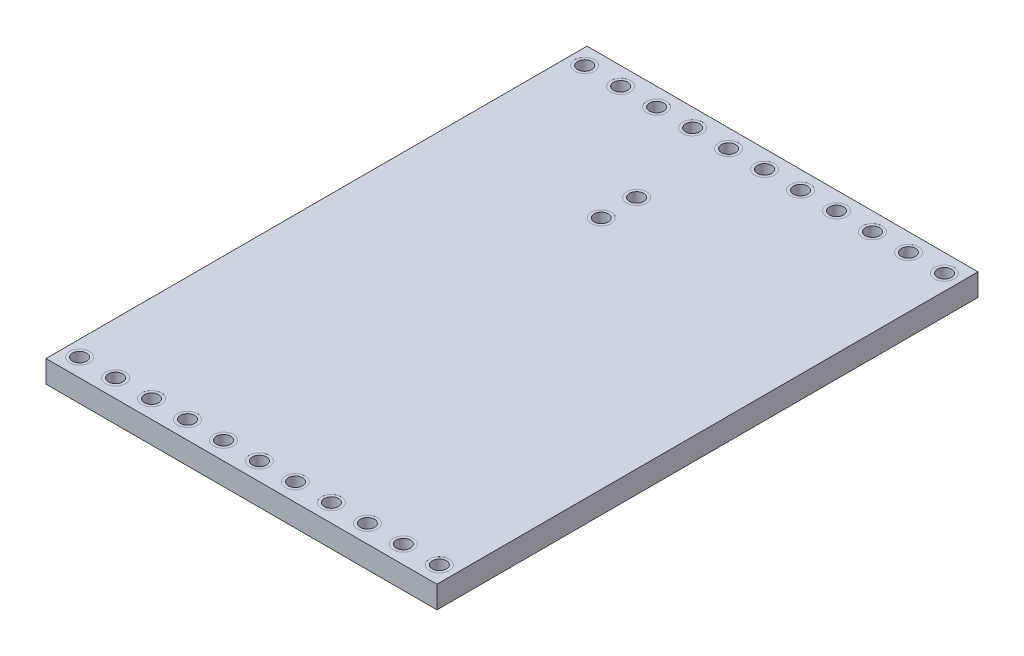
SolidWorks part; units mm, degrees
material "Power Circuit Board"
ref_plane "Front Plane" through (0, 0, 0) normal (0, 0, 1) x (1, 0, 0)
ref_plane "Top Plane" through (0, 0, 0) normal (0, 1, 0) x (1, 0, 0)
ref_plane "Right Plane" through (0, 0, 0) normal (1, 0, 0) x (0, 0, -1)
sketch "BaseS" plane through (0, 0, 0) normal (0, 1, 0) x (1, 0, 0)
  line L1 (-13.8, 19.1) -> (13.8, 19.1)
  line L2 (-13.8, 19.1) -> (-13.8, -19.1)
  line L3 (-13.8, -19.1) -> (13.8, -19.1)
  line L4 (13.8, 19.1) -> (13.8, -19.1)
  line L5 (-13.8, 19.1) -> (13.8, -19.1) construction
  line L6 (-13.8, -19.1) -> (13.8, 19.1) construction
  point P0 (0, 0)
  dimension "Width" = 27.6
  dimension "Length" = 38.2
extrude "Base" add sketch "BaseS" against normal mid plane 1.57
hole_wizard "Ø1.0 (1) Diameter Hole1" positions "Sketch2" profile "Sketch3" hole size "Ø1.0" standard "ANSI Metric" end condition through all
sketch "Sketch2" plane through (0, 0.785, 0) normal (0, 1, 0) x (1, 0, 0)
  line L0 (-13.8, 19.1) -> (-13.8, -19.1) construction
  line L1 (-13.8, -19.1) -> (13.8, -19.1) construction
  point P0 (-12.7, -17.83)
  dimension "XDim" = 1.1
  dimension "YDim" = 1.27
sketch "Sketch3" plane through (-12.7, 0.785, 17.83) normal (1, 0, 0) x (0, 0, 1)
  line L0 (0, 0) -> (0, 1.57)
  line L1 (0, 1.57) -> (0.5, 1.57)
  line L2 (0.5, 1.57) -> (0.5, 0)
  line L5 (0.5, 0) -> (0, 0)
  line L11 (0, -6.35) -> (0, 107.95) construction
  dimension "Thru Hole Dia." = 1
  dimension "Thru Hole Depth" = 1.57
sketch "SolderAccessCutS" plane through (0, 0.785, 0) normal (0, 1, 0) x (1, 0, 0)
  circle A3 centre (-12.7, -17.83) radius 0.7
  dimension "Dia" = 1.4
extrude "SolderAccessCut" cut sketch "SolderAccessCutS" against normal blind 0.001
mirror "SACVM" about plane through (0, 0, 0) normal (0, 1, 0) of "SolderAccessCut"
pattern_linear "HoleSACHorzLP" count 11 spacing 2.54 along (1, 0, 0) of "Ø1.0 (1) Diameter Hole1", "SolderAccessCut", "SACVM"
mirror "Mirror1" about plane through (0, 0, 0) normal (0, 0, 1) of "HoleSACHorzLP", "SACVM", "SolderAccessCut", "Ø1.0 (1) Diameter Hole1"
hole_wizard "Ø1.0 (1) Diameter Hole2" positions "Sketch4" profile "Sketch5" hole size "Ø1.0" standard "ANSI Metric" end condition through all
sketch "Sketch4" plane through (0, 0.785, 0) normal (0, 1, 0) x (1, 0, 0)
  line L0 (-2.8, 11.6) -> (-2.8, 9.1) construction
  line L2 (-13.8, 19.1) -> (-13.8, -19.1) construction
  line L3 (13.8, 19.1) -> (-13.8, 19.1) construction
  point P0 (-2.8, 11.6)
  point P2 (-2.8, 9.1)
  dimension "XDim" = 11
  dimension "Distance" = 2.5
  dimension "YDim" = 7.5
sketch "Sketch5" plane through (-2.8, 0.785, -11.6) normal (1, 0, 0) x (0, 0, 1)
  line L0 (0, 0) -> (0, 1.57)
  line L1 (0, 1.57) -> (0.5, 1.57)
  line L2 (0.5, 1.57) -> (0.5, 0)
  line L5 (0.5, 0) -> (0, 0)
  line L11 (0, -6.35) -> (0, 107.95) construction
  dimension "Thru Hole Dia." = 1
  dimension "Thru Hole Depth" = 1.57
sketch "SolderAccessCutforCapacitorS" plane through (0, 0.785, 0) normal (0, 1, 0) x (1, 0, 0)
  circle A0 centre (-2.8, 11.6) radius 0.7
  circle A1 centre (-2.8, 9.1) radius 0.7
  circle A2 centre (-2.8, 9.1) radius 0.5 construction
  circle A3 centre (-2.8, 11.6) radius 0.5 construction
  circle A4 centre (-2.8, 9.1) radius 0.5
  circle A5 centre (-2.8, 11.6) radius 0.5
  dimension "Dia" = 1.4
extrude "SolderAccessCutforCapacitor" cut sketch "SolderAccessCutforCapacitorS" against normal blind 0.001
mirror "SACCVM" about plane through (0, 0, 0) normal (0, 1, 0) of "SolderAccessCutforCapacitor"
